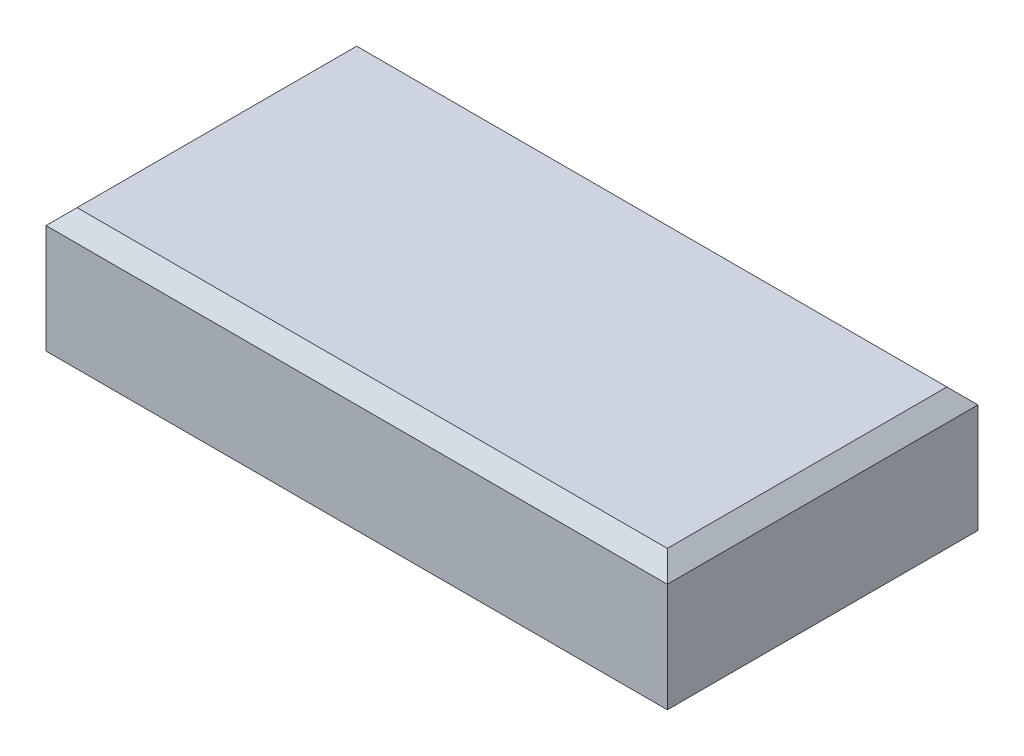
SolidWorks part; units mm, degrees
ref_plane "Front Plane" through (0, 0, 0) normal (0, 0, 1) x (1, 0, 0)
ref_plane "Top Plane" through (0, 0, 0) normal (0, 1, 0) x (1, 0, 0)
ref_plane "Right Plane" through (0, 0, 0) normal (1, 0, 0) x (0, 0, -1)
sketch "Sketch1" plane through (0, 0, 0) normal (0, 1, 0) x (1, 0, 0)
  line L1 (-20, -7.6815) -> (20, -7.6815)
  line L2 (-20, -7.6815) -> (-20, 12.3185)
  line L3 (-20, 12.3185) -> (20, 12.3185)
  line L4 (20, -7.6815) -> (20, 12.3185)
  line L5 (-20, -7.6815) -> (20, 12.3185) construction
  line L6 (-20, 12.3185) -> (20, -7.6815) construction
  point P0 (0, 2.3185)
  dimension "D1" = 40
  dimension "D2" = 20
extrude "Boss-Extrude1" add sketch "Sketch1" along normal blind 8
chamfer "Chamfer1" distance 1 angle 45 4 edges at (0, 8, 7.6815) (-20, 8, -2.3185) (0, 8, -12.3185) (20, 8, -2.3185)
